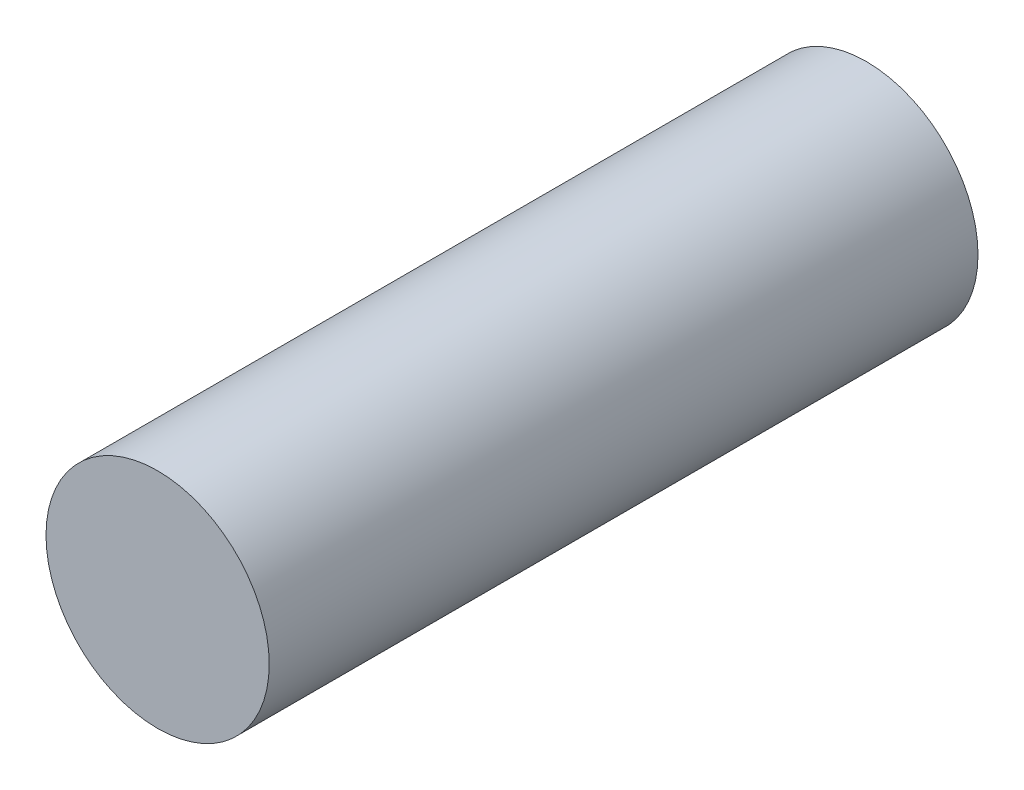
SolidWorks part; units mm, degrees
material "6061 Alloy"
ref_plane "Front Plane" through (0, 0, 0) normal (0, 0, 1) x (1, 0, 0)
ref_plane "Top Plane" through (0, 0, 0) normal (0, 1, 0) x (1, 0, 0)
ref_plane "Right Plane" through (0, 0, 0) normal (1, 0, 0) x (0, 0, -1)
sketch "Sketch1" plane through (0, 0, 0) normal (0, 0, 1) x (1, 0, 0)
  line L0 (-3, 0) -> (3, 0) construction
  point P4 (0, 0)
  dimension "OD" = 6
sketch "Sketch2" plane through (0, 0, 0) normal (1, 0, 0) x (0, 0, -1)
  line L0 (9.525, 0) -> (-9.525, 0) construction
  line L1 (-9.525, 3) -> (-9.525, -3) construction
  line L2 (9.525, 3) -> (9.525, -3) construction
  point P0 (-2.625, 0)
  point P4 (0, 0)
  point P6 (2.625, 0)
  point P10 (9.525, 0)
  point P12 (-9.525, 0)
  dimension "Length" = 19.05
  dimension "D1" = 6.9
  dimension "D2" = 6.9
  dimension "D3" = 6
sketch "Sketch3" plane through (0, 0, 0) normal (0, 0, 1) x (1, 0, 0)
  circle A0 centre (0, 0) radius 3
extrude "Boss-Extrude1" add sketch "Sketch3" along normal mid plane 19.05
chamfer "Chamfer1" [suppressed] distance 0.3 angle 45
fillet "Fillet2" [suppressed] radius 0.225
equation "\"D1@Boss-Extrude1\"=\"Length@Sketch2\""
equation "\"D1@Chamfer1\"=\"OD@Sketch1\"*.05"
equation "\"D1@Fillet2\"=\"D1@Chamfer1\"*.75"
equation "\"D3@Sketch2\"=\"OD@Sketch1\""
equation "\"D1@Sketch2\"=\"OD@Sketch1\"*1.15"
equation "\"D2@Sketch2\"=\"D1@Sketch2\""
